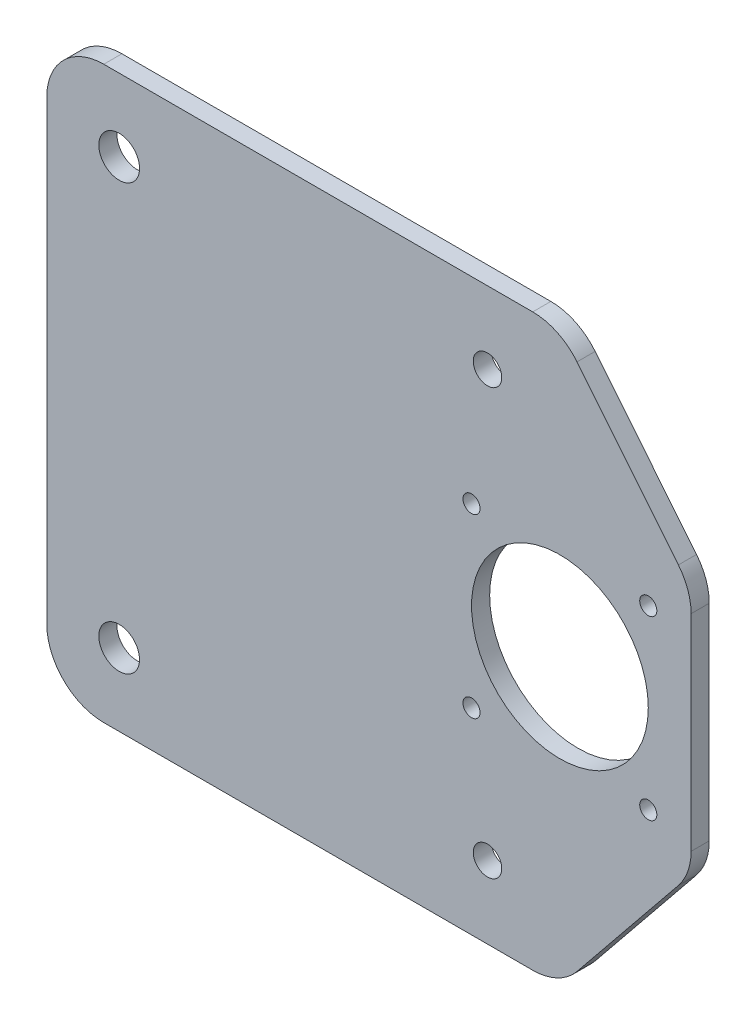
SolidWorks part; units mm, degrees
ref_plane "Front Plane" through (0, 0, 0) normal (0, 0, 1) x (1, 0, 0)
ref_plane "Top Plane" through (0, 0, 0) normal (0, 1, 0) x (1, 0, 0)
ref_plane "Right Plane" through (0, 0, 0) normal (1, 0, 0) x (0, 0, -1)
sketch "Sketch1" plane through (0, 0, 0) normal (0, 0, 1) x (1, 0, 0)
  line L0 (35, 45) -> (-35, 45) construction
  line L1 (-45, -55) -> (45, -55)
  line L2 (-45, -55) -> (-45, 45)
  line L3 (-45, 45) -> (45, 45)
  line L4 (45, -55) -> (45, 45)
  line L5 (-43.1231, -55) -> (43.1231, -55) construction
  line L6 (-45, 35) -> (-45, 25) construction
  line L7 (45, 25) -> (45, 35) construction
  circle A1 centre (32.3, -42.3) radius 2.5 construction
  circle A2 centre (-32.3, -42.3) radius 3.57 construction
  circle A5 centre (32.3, -42.3) radius 2.5
  circle A6 centre (-32.3, -42.3) radius 3.57
  circle A8 centre (-32.3, 32.3) radius 3.57 construction
  circle A9 centre (-32.3, 32.3) radius 3.57
  circle A10 centre (32.3, 32.3) radius 2.5 construction
  circle A11 centre (32.3, 32.3) radius 2.5
extrude "Boss-Extrude1" add sketch "Sketch1" against normal blind 3.18 from vertex
sketch "Sketch2" plane through (0, 0, 18.7298) normal (0, 0, 1) x (1, 0, 0)
  line L0 (45, 45) -> (68.0122, 16.59)
  line L1 (68.0122, 16.59) -> (68.0122, -26.59)
  line L2 (68.0122, -26.59) -> (45, -55)
  line L3 (45, -55) -> (45, 45)
  line L4 (45, -5) -> (68.0122, -5) construction
  dimension "D1" = 43.18
extrude "Boss-Extrude2" add sketch "Sketch2" against normal through all
sketch "Sketch3" plane through (0, 0, 18.7298) normal (0, 0, 1) x (1, 0, 0)
  line L0 (45, 45) -> (45, -55) construction
  line L2 (29.5, 10.5) -> (60.5, 10.5) construction
  line L3 (29.5, 10.5) -> (29.5, -20.5) construction
  line L4 (29.5, -20.5) -> (60.5, -20.5) construction
  line L5 (60.5, 10.5) -> (60.5, -20.5) construction
  line L6 (29.5, 10.5) -> (60.5, -20.5) construction
  line L7 (29.5, -20.5) -> (60.5, 10.5) construction
  circle A0 centre (29.5, 10.5) radius 1.5
  circle A1 centre (60.5, 10.5) radius 1.5
  circle A2 centre (60.5, -20.5) radius 1.5
  circle A3 centre (29.5, -20.5) radius 1.5
  circle A4 centre (45, -5) radius 15.5
  point P4 (45, -5)
  dimension "D2" = 3
  dimension "D3" = 31
  dimension "D1" = 31
extrude "Cut-Extrude1" cut sketch "Sketch3" against normal blind 10
fillet "Fillet1" radius 10 6 edges at (-45, -55, 17.1398) (-45, 45, 17.1398) (45, -55, 17.1398) (68.0122, -26.59, 17.1398) (68.0122, 16.59, 17.1398) (45, 45, 17.1398)
